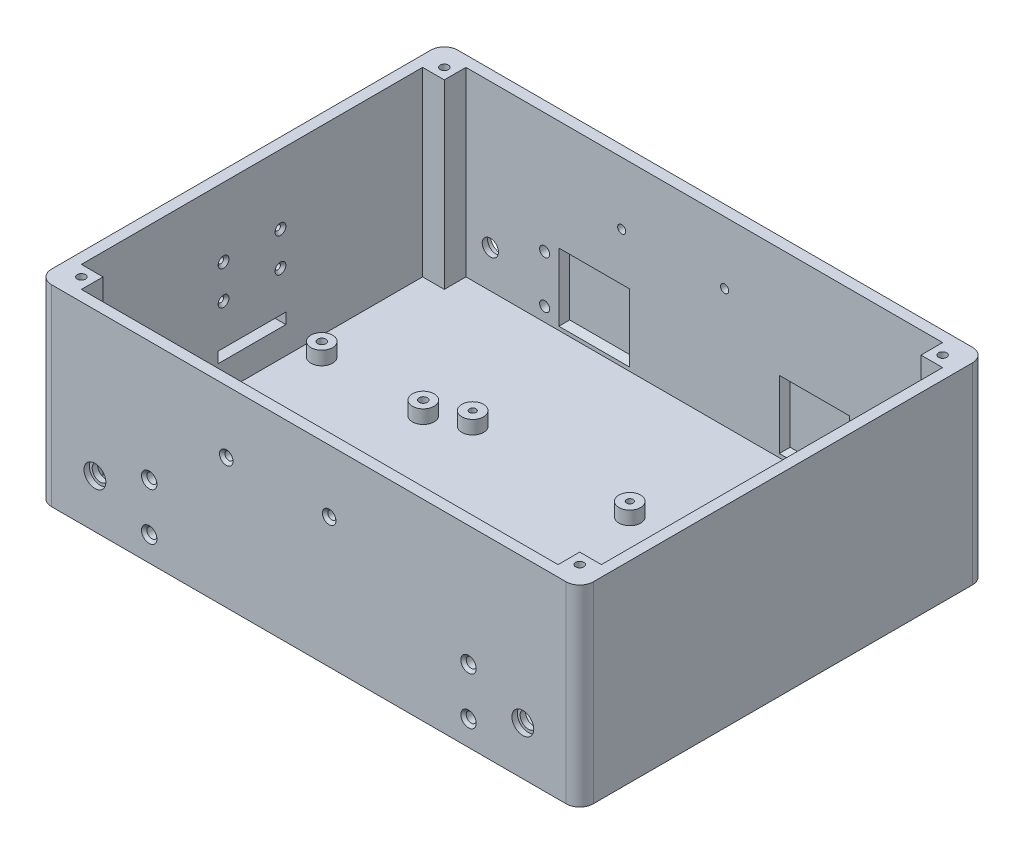
SolidWorks part; units mm, degrees
ref_plane "Płaszczyzna przednia" through (0, 0, 0) normal (0, 0, 1) x (1, 0, 0)
ref_plane "Płaszczyzna górna" through (0, 0, 0) normal (0, 1, 0) x (1, 0, 0)
ref_plane "Płaszczyzna prawa" through (0, 0, 0) normal (1, 0, 0) x (0, 0, -1)
sketch "Szkic2" plane through (0, 0, 0) normal (0, 1, 0) x (1, 0, 0)
  line L1 (-100, 75) -> (100, 75)
  line L2 (-100, 75) -> (-100, -75)
  line L3 (-100, -75) -> (100, -75)
  line L4 (100, 75) -> (100, -75)
  line L5 (-100, 75) -> (100, -75) construction
  line L6 (-100, -75) -> (100, 75) construction
  point P0 (0, 0)
  dimension "D1" = 200
  dimension "D2" = 150
extrude "Dodanie-wyciągnięcie1" add sketch "Szkic2" along normal blind 41
shell "Skorupa1" thickness 4
sketch "Szkic3" plane through (0, 0, -71) normal (0, 0, 1) x (1, 0, 0)
  line L0 (-96, 41) -> (-79, 41) construction
  line L1 (96, 41) -> (-96, 41) construction
  line L2 (-79, 41) -> (-79, 17.875) construction
  line L3 (-96, 41) -> (-58.2, 41) construction
  line L4 (-79, 17.875) -> (-58.95, 17.875) construction
  line L5 (-58.95, 17.875) -> (-58.95, 26.625) construction
  line L6 (-58.95, 17.875) -> (-58.95, 9.125) construction
  line L7 (79, 41) -> (79, 17.875) construction
  line L8 (96, 41) -> (96, 4) construction
  line L9 (79, 17.875) -> (58.95, 17.875) construction
  line L10 (58.95, 17.875) -> (58.95, 26.625) construction
  line L11 (58.95, 17.875) -> (58.95, 9.125) construction
  circle A0 centre (-79, 17.875) radius 3
  circle A1 centre (-58.95, 26.625) radius 1.85
  circle A2 centre (-58.95, 9.125) radius 1.85
  circle A3 centre (79, 17.875) radius 3
  circle A4 centre (58.95, 26.625) radius 1.85
  circle A5 centre (58.95, 9.125) radius 1.85
  dimension "D3" = 6
  dimension "D6" = 8.75
  dimension "D8" = 3.7
  dimension "D7" = 3.7
  dimension "D11" = 6
  dimension "D15" = 3.7
  dimension "D16" = 3.7
  dimension "D1" = 17
  dimension "D2" = 23.125
  dimension "D4" = 20.05
  dimension "D5" = 8.75
  dimension "D9" = 23.125
  dimension "D10" = 17
  dimension "D12" = 20.05
  dimension "D13" = 8.75
  dimension "D14" = 8.75
extrude "Wytnij-wyciągnięcie2" cut sketch "Szkic3" against normal blind 15 and the other way blind 167
sketch "Szkic4" plane through (0, 0, -75) normal (0, 0, -1) x (-1, 0, 0)
  circle A0 centre (-79, 17.875) radius 4.035
  circle A1 centre (79, 17.875) radius 4.035
  dimension "D1" = 8.07
  dimension "D2" = 8.07
extrude "Wytnij-wyciągnięcie3" cut sketch "Szkic4" against normal blind 2
sketch "Szkic5" plane through (0, 0, 75) normal (0, 0, 1) x (1, 0, 0)
  circle A0 centre (79, 17.875) radius 4.035
  circle A1 centre (-79, 17.875) radius 4.035
  dimension "D1" = 8.07
  dimension "D2" = 8.07
extrude "Wytnij-wyciągnięcie4" cut sketch "Szkic5" against normal blind 2
sketch "Szkic6" plane through (0, 4, 0) normal (0, 1, 0) x (1, 0, 0)
  line L0 (-96, 71) -> (-96, -71) construction
  line L2 (-39, 0) -> (-39, 24.5) construction
  line L3 (-39, 0) -> (-39, -24.5) construction
  line L4 (-39, -24.5) -> (19, -24.5) construction
  line L5 (19, -24.5) -> (19, 24.5) construction
  line L6 (-96, 0) -> (-83.4501, 0) construction
  circle A0 centre (19, -24.5) radius 4
  circle A1 centre (19, 24.5) radius 4
  circle A2 centre (-39, 24.5) radius 4
  circle A3 centre (-39, -24.5) radius 4
  dimension "D5" = 8
  dimension "D6" = 8
  dimension "D7" = 8
  dimension "D8" = 8
  dimension "D2" = 24.5
  dimension "D3" = 24.5
  dimension "D4" = 58
  dimension "D9" = 49
  dimension "D10" = 57
extrude "Dodanie-wyciągnięcie2" add sketch "Szkic6" along normal blind 5
sketch "Szkic7" plane through (0, 9, 0) normal (0, 1, 0) x (1, 0, 0)
  circle A0 centre (-39, 24.5) radius 1.2
  circle A1 centre (19, 24.5) radius 1.2
  circle A2 centre (19, -24.5) radius 1.2
  circle A3 centre (-39, -24.5) radius 1.2
  dimension "D1" = 2.4
  dimension "D2" = 2.4
  dimension "D3" = 2.4
  dimension "D4" = 2.4
extrude "Wytnij-wyciągnięcie5" cut sketch "Szkic7" against normal blind 10
sketch "Szkic9" plane through (0, 0, -71) normal (0, 0, 1) x (1, 0, 0)
  line L0 (-96, 17.875) -> (-53.7, 17.875) construction
  line L1 (-96, 41) -> (-96, 4) construction
  line L2 (-53.7, 30.375) -> (-53.7, 5.375)
  line L3 (-53.7, 30.375) -> (-27.7, 30.375)
  line L4 (-27.7, 30.375) -> (-27.7, 5.375)
  line L5 (-27.7, 5.375) -> (-53.7, 5.375)
  point P8 (-53.7, 17.875)
  dimension "D1" = 42.3
  dimension "D2" = 25
  dimension "D3" = 26
extrude "Wytnij-wyciągnięcie7" cut sketch "Szkic9" against normal blind 2 draft 45
sketch "Szkic10" plane through (0, 0, -71) normal (0, 0, 1) x (1, 0, 0)
  line L0 (96, 17.875) -> (53.7, 17.875) construction
  line L1 (96, 41) -> (96, 4) construction
  line L2 (53.7, 30.375) -> (53.7, 5.375)
  line L3 (53.7, 5.375) -> (27.7, 5.375)
  line L4 (27.7, 5.375) -> (27.7, 30.375)
  line L5 (27.7, 30.375) -> (53.7, 30.375)
  point P8 (53.7, 17.875)
  dimension "D1" = 42.3
  dimension "D2" = 25
  dimension "D3" = 26
extrude "Wytnij-wyciągnięcie8" cut sketch "Szkic10" against normal blind 2 draft 45
sketch "Szkic11" plane through (0, 0, 71) normal (0, 0, -1) x (-1, 0, 0)
  line L0 (96, 17.875) -> (53.7, 17.875) construction
  line L1 (96, 41) -> (96, 4) construction
  line L2 (53.7, 30.375) -> (53.7, 5.375)
  line L3 (53.7, 5.375) -> (27.7, 5.375)
  line L4 (27.7, 5.375) -> (27.7, 30.375)
  line L5 (27.7, 30.375) -> (53.7, 30.375)
  point P8 (53.7, 17.875)
  dimension "D1" = 42.3
  dimension "D2" = 25
  dimension "D3" = 26
extrude "Wytnij-wyciągnięcie9" cut sketch "Szkic11" against normal blind 2 draft 45
sketch "Szkic12" plane through (0, 0, 71) normal (0, 0, -1) x (-1, 0, 0)
  line L0 (-96, 17.875) -> (-53.7, 17.875) construction
  line L2 (-53.7, 30.375) -> (-53.7, 5.375)
  line L3 (-53.7, 30.375) -> (-27.7, 30.375)
  line L4 (-27.7, 30.375) -> (-27.7, 5.375)
  line L5 (-27.7, 5.375) -> (-53.7, 5.375)
  line L6 (-96, 41) -> (-96, 4) construction
  point P8 (-53.7, 17.875)
  dimension "D1" = 42.3
  dimension "D2" = 25
  dimension "D3" = 26
extrude "Wytnij-wyciągnięcie10" cut sketch "Szkic12" against normal blind 2 draft 45
sketch "Szkic13" plane through (0, 4, 0) normal (0, 1, 0) x (1, 0, 0)
  line L0 (-89, 0) -> (-96, 0) construction
  line L2 (-51.5, 0) -> (-51.5, 18.75) construction
  line L3 (-51.5, 18.75) -> (-89, 18.75) construction
  line L4 (-89, 18.75) -> (-89, -18.75) construction
  line L5 (-89, -18.75) -> (-51.5, -18.75) construction
  line L6 (-51.5, -18.75) -> (-51.5, 0) construction
  line L8 (-96, 71) -> (-96, -71) construction
  circle A0 centre (-51.5, 18.75) radius 4
  circle A1 centre (-89, 18.75) radius 4
  circle A2 centre (-89, -18.75) radius 4
  circle A3 centre (-51.5, -18.75) radius 4
  dimension "D5" = 8
  dimension "D6" = 8
  dimension "D7" = 8
  dimension "D8" = 8
  dimension "D1" = 7
  dimension "D2" = 18.75
  dimension "D3" = 18.75
  dimension "D4" = 37.5
extrude "Dodanie-wyciągnięcie3" add sketch "Szkic13" along normal blind 5
sketch "Szkic14" plane through (0, 9, 0) normal (0, 1, 0) x (1, 0, 0)
  line L0 (96, -71) -> (96, 71) construction
  circle A0 centre (-51.5, 18.75) radius 1.5
  circle A1 centre (-89, 18.75) radius 1.5
  circle A2 centre (-89, -18.75) radius 1.5
  circle A3 centre (-51.5, -18.75) radius 1.5
  dimension "D1" = 3
  dimension "D2" = 3
  dimension "D3" = 3
  dimension "D4" = 3
  dimension "D5" = 147.5
extrude "Wytnij-wyciągnięcie11" cut sketch "Szkic14" against normal blind 20
sketch "Szkic15" plane through (0, 41, 0) normal (0, 1, 0) x (1, 0, 0)
  line L0 (-100, 75) -> (100, 75)
  line L1 (100, 75) -> (100, -75)
  line L2 (100, -75) -> (-100, -75)
  line L3 (-100, -75) -> (-100, 75)
  line L4 (-96, 71) -> (-96, -71)
  line L5 (-96, -71) -> (96, -71)
  line L6 (96, -71) -> (96, 71)
  line L7 (96, 71) -> (-96, 71)
extrude "Dodanie-wyciągnięcie4" add sketch "Szkic15" along normal blind 30
sketch "Szkic18" plane through (0, 0, -75) normal (0, 0, -1) x (-1, 0, 0)
  line L0 (100, 48) -> (30.5, 48) construction
  line L1 (100, 71) -> (100, 0) construction
  line L2 (-100, 71) -> (100, 71) construction
  line L3 (30.5, 48) -> (-7.5, 48) construction
  circle A0 centre (30.5, 48) radius 1.5
  circle A1 centre (-7.5, 48) radius 1.5
  dimension "D4" = 3
  dimension "D5" = 3
  dimension "D1" = 69.5
  dimension "D2" = 23
  dimension "D3" = 38
extrude "Wytnij-wyciągnięcie12" cut sketch "Szkic18" against normal blind 170
chamfer "Sfazowanie4" distance 1 angle 45 12 edges at (-60.8, 9.125, 75) (57.1, 9.125, 75) (57.1, 26.625, 75) (6, 48, 75) (-32, 48, 75) (-60.8, 26.625, 75) (-57.1, 9.125, -75) (-57.1, 26.625, -75) (6, 48, -75) (-32, 48, -75) (60.8, 9.125, -75) (60.8, 26.625, -75)
fillet "Zaokrąglenie2" radius 5 1 edges at (-100, 35.5, 75)
fillet "Zaokrąglenie3" radius 5 1 edges at (-100, 35.5, -75)
fillet "Zaokrąglenie4" radius 5 1 edges at (100, 35.5, -75)
fillet "Zaokrąglenie5" radius 5 1 edges at (100, 35.5, 75)
sketch "Szkic20" plane through (-100, 0, 0) normal (-1, 0, 0) x (0, 0, 1)
  line L0 (0, 0) -> (0, 16) construction
  line L1 (-70, 0) -> (70, 0) construction
  line L3 (-12.5, 14) -> (12.5, 14)
  line L4 (-12.5, 14) -> (-12.5, 18)
  line L5 (-12.5, 18) -> (12.5, 18)
  line L6 (12.5, 14) -> (12.5, 18)
  line L7 (-12.5, 14) -> (12.5, 18) construction
  line L8 (-12.5, 18) -> (12.5, 14) construction
  dimension "D1" = 25
  dimension "D2" = 4
  dimension "D3" = 16
extrude "Wytnij-wyciągnięcie13" cut sketch "Szkic20" against normal blind 10
sketch "Szkic21" plane through (0, 4, 0) normal (0, 1, 0) x (1, 0, 0)
  line L1 (-96, 71) -> (-88, 71)
  line L2 (-96, 71) -> (-96, 63)
  line L3 (-96, 63) -> (-88, 63)
  line L4 (-88, 71) -> (-88, 63)
  line L5 (-96, -71) -> (-88, -71)
  line L6 (-96, -71) -> (-96, -63)
  line L7 (-96, -63) -> (-88, -63)
  line L8 (-88, -71) -> (-88, -63)
  line L9 (96, -71) -> (88, -71)
  line L10 (96, -71) -> (96, -63)
  line L11 (96, -63) -> (88, -63)
  line L12 (88, -71) -> (88, -63)
  line L13 (96, 71) -> (88, 71)
  line L14 (96, 71) -> (96, 63)
  line L15 (96, 63) -> (88, 63)
  line L16 (88, 71) -> (88, 63)
  circle A0 centre (-92, -67) radius 1.5
  circle A1 centre (-92, 67) radius 1.5
  circle A2 centre (92, 67) radius 1.5
  circle A3 centre (92, -67) radius 1.5
  dimension "D5" = 3
  dimension "D6" = 3
  dimension "D7" = 3
  dimension "D8" = 3
  dimension "D1" = 8
  dimension "D2" = 8
  dimension "D3" = 8
  dimension "D4" = 8
extrude "Dodanie-wyciągnięcie5" add sketch "Szkic21" along normal blind 67
sketch "Szkic22" plane through (0, 4, 0) normal (0, 1, 0) x (1, 0, 0)
  line L0 (96, -63) -> (96, 63) construction
  line L2 (89, 0) -> (89, 18.75) construction
  line L3 (89, 18.75) -> (51.5, 18.75) construction
  line L4 (51.5, 18.75) -> (51.5, -18.75) construction
  line L5 (51.5, -18.75) -> (89, -18.75) construction
  line L6 (89, -18.75) -> (89, 0) construction
  line L7 (-88, -71) -> (88, -71) construction
  circle A0 centre (89, 18.75) radius 4
  circle A1 centre (51.5, 18.75) radius 4
  circle A2 centre (51.5, -18.75) radius 4
  circle A3 centre (89, -18.75) radius 4
  dimension "D5" = 8
  dimension "D6" = 8
  dimension "D7" = 8
  dimension "D8" = 8
  dimension "D1" = 7
  dimension "D2" = 18.75
  dimension "D3" = 18.75
  dimension "D4" = 37.5
  dimension "D9" = 52.25
extrude "Dodanie-wyciągnięcie6" add sketch "Szkic22" along normal blind 5
sketch "Szkic23" plane through (0, 9, 0) normal (0, 1, 0) x (1, 0, 0)
  circle A0 centre (51.5, 18.75) radius 1.5
  circle A1 centre (89, 18.75) radius 1.5
  circle A2 centre (51.5, -18.75) radius 1.5
  circle A3 centre (89, -18.75) radius 1.5
  dimension "D1" = 3
  dimension "D2" = 3
  dimension "D3" = 3
  dimension "D4" = 3
extrude "Wytnij-wyciągnięcie14" cut sketch "Szkic23" against normal blind 10
sketch "Szkic24" plane through (-100, 0, 0) normal (-1, 0, 0) x (0, 0, 1)
  line L0 (0, 18) -> (0, 33) construction
  line L1 (12.5, 18) -> (-12.5, 18) construction
  line L2 (0, 33) -> (-10.5, 33) construction
  line L3 (-10.5, 33) -> (-10.5, 45.5) construction
  line L4 (-10.5, 45.5) -> (10.5, 45.5) construction
  line L5 (10.5, 45.5) -> (10.5, 33) construction
  line L6 (10.5, 33) -> (0, 33) construction
  circle A0 centre (-10.5, 33) radius 1
  circle A1 centre (-10.5, 45.5) radius 1
  circle A2 centre (10.5, 45.5) radius 1
  circle A3 centre (10.5, 33) radius 1
  dimension "D6" = 2
  dimension "D7" = 2
  dimension "D8" = 2
  dimension "D9" = 2
  dimension "D1" = 15
  dimension "D2" = 10.5
  dimension "D3" = 12.5
  dimension "D4" = 21
  dimension "D5" = 12.5
extrude "Wytnij-wyciągnięcie15" cut sketch "Szkic24" against normal blind 5
chamfer "Sfazowanie5" distance 1 angle 45 4 edges at (-96, 33, 9.5) (-96, 45.5, 9.5) (-96, 45.5, -11.5) (-96, 33, -11.5)
